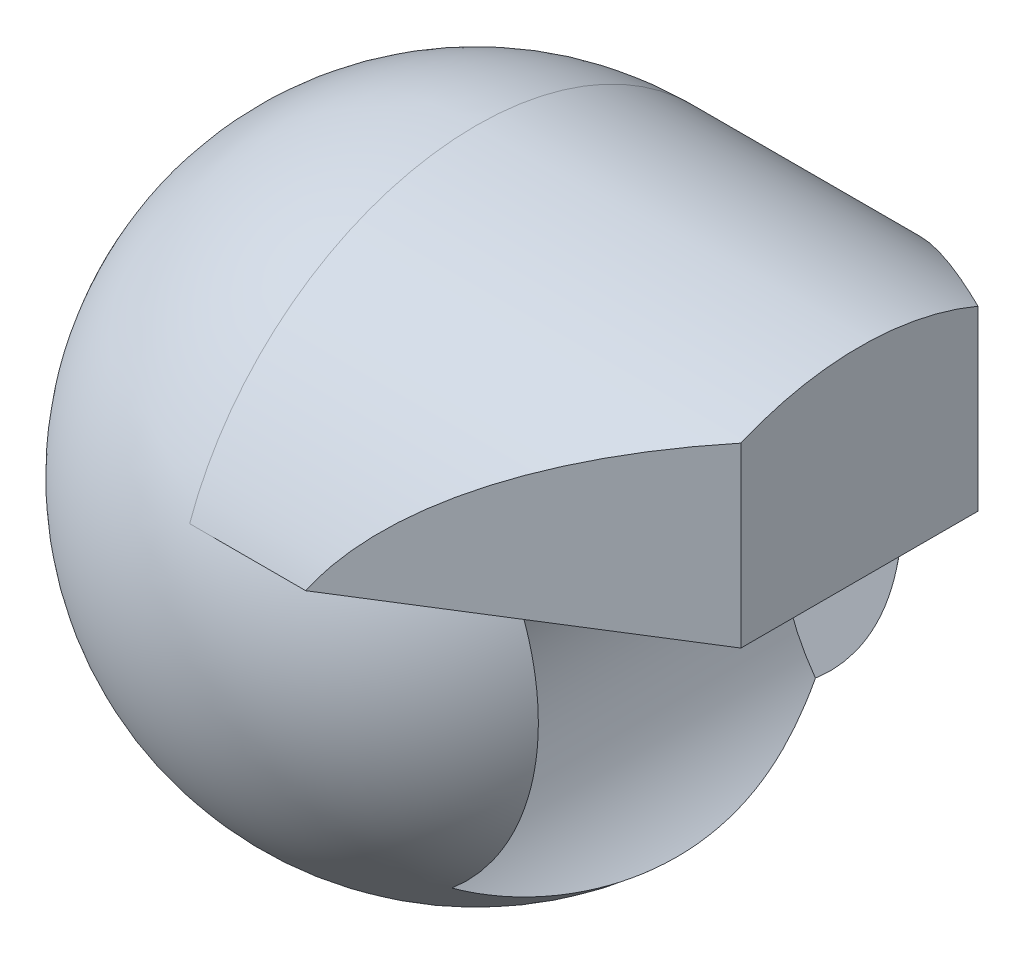
SolidWorks part; units mm, degrees
ref_plane "Front Plane" through (0, 0, 0) normal (0, 0, 1) x (1, 0, 0)
ref_plane "Top Plane" through (0, 0, 0) normal (0, 1, 0) x (1, 0, 0)
ref_plane "Right Plane" through (0, 0, 0) normal (1, 0, 0) x (0, 0, -1)
sketch "Sketch1" plane through (0, 0, 0) normal (0, 0, 1) x (1, 0, 0)
  line L0 (-1003.3883, 0) -> (48996.6117, 0) construction
  line L1 (0, -1000) -> (0, 49000) construction
  line L2 (-97.79, -981.2017) -> (-97.79, 49018.7983) construction
  line L3 (-1101.1783, 25.4) -> (48898.8217, 25.4) construction
  line L4 (-195.58, 25.4) -> (0, 25.4)
  arc A1 (0, 25.4) -> (-195.58, 25.4) centre (-97.79, 25.4) ccw
  dimension "D1" = 97.79
  dimension "D2" = 195.58
  dimension "D3" = 25.4
  dimension "D5" = 195.58
revolve "Revolve1" add sketch "Sketch1" angle 360 about L4
sketch "Sketch2" plane through (0, 0, 0) normal (1, 0, 0) x (0, 0, -1)
  line L0 (-1000, 123.19) -> (49000, 123.19) construction
  line L3 (-92.0465, 58.42) -> (92.0465, 58.42)
  line L7 (0, -1000) -> (0, 49000) construction
  circle A1 centre (0, 25.4) radius 97.79 construction
  arc A2 (92.0465, 58.42) -> (-92.0465, 58.42) centre (0, 25.4) ccw
  dimension "D1" = 58.42
extrude "Boss-Extrude2" add sketch "Sketch2" along normal blind 25.4 and the other way blind 97.79
sketch "Sketch3" plane through (0, 0, 0) normal (0, 1, 0) x (1, 0, 0)
  line L0 (25.4, -38.1) -> (25.4, 38.1)
  line L1 (25.4, 38.1) -> (-97.79, 115.4825)
  line L2 (-97.79, 115.4825) -> (50.8, 115.4825)
  line L3 (50.8, 115.4825) -> (50.8, -115.4825)
  line L4 (-1000, 0) -> (49000, 0) construction
  line L5 (-97.79, -1000) -> (-97.79, 49000) construction
  line L6 (-97.79, 92.0465) -> (-97.79, -92.0465) construction
  line L8 (25.4, -92.0465) -> (25.4, 92.0465) construction
  line L9 (-97.79, -115.4825) -> (50.8, -115.4825)
  line L10 (25.4, -38.1) -> (-97.79, -115.4825)
  circle A0 centre (-97.79, 0) radius 97.79 construction
  point P13 (-97.79, 0)
  point P20 (50.8, 0)
  point P21 (25.4, 0)
  dimension "D1" = 38.1
  dimension "D3" = 25.4
extrude "Cut-Extrude1" cut sketch "Sketch3" along normal through all
sketch "Sketch4" plane through (0, 0, 0) normal (0, 0, 1) x (1, 0, 0)
  circle A0 centre (0, 0) radius 58.42
  dimension "D1" = 116.84
extrude "Cut-Extrude2" cut sketch "Sketch4" against normal blind 58.42 and the other way blind 58.42
sketch3d "3DSketch1"
  line L0 (0, 0, -127) -> (0, 0, 127) construction
  line L1 (-97.79, -981.2017, 0) -> (-97.79, 49018.7983, 0) construction
  line L4 (25.4, 123.19, 0) -> (25.4, 25.4, 0)
  line L6 (-1101.1783, 25.4, 0) -> (48898.8217, 25.4, 0) construction
  line L7 (25.4, 25.4, 0) -> (-195.58, 25.4, 0)
  arc A0 (0, 25.4, 0) -> (-195.58, 25.4, 0) centre (-97.79, 25.4, 0) ccw construction
  arc A1 (25.4, 115.4626, -38.1) -> (25.4, 115.4626, 38.1) centre (25.4, 25.4, 0) ccw construction
  point P0 (-97.79, -72.39, 0)
  point P9 (-97.79, 25.4, 97.79)
  point P16 (123.19, 25.4, 0)
  point P21 (-85.09, 25.4, 0)
  dimension "D1" = 254
